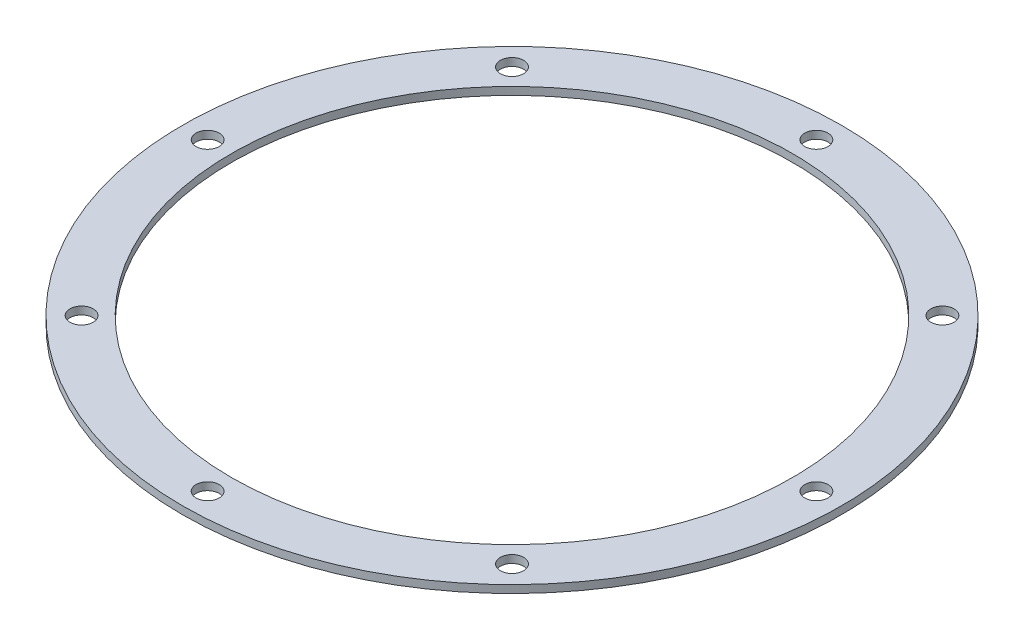
SolidWorks part; units mm, degrees
ref_plane "Front Plane" through (0, 0, 0) normal (0, 0, 1) x (1, 0, 0)
ref_plane "Top Plane" through (0, 0, 0) normal (0, 1, 0) x (1, 0, 0)
ref_plane "Right Plane" through (0, 0, 0) normal (1, 0, 0) x (0, 0, -1)
sketch "Sketch1" plane through (0, 0, 0) normal (0, 1, 0) x (1, 0, 0)
  circle A0 centre (0, 0) radius 72.375
  circle A1 centre (0, 0) radius 85
  circle A2 centre (0, 0) radius 78.5
  dimension "D1" = 157
  dimension "D2" = 170
  dimension "D3" = 144.75
extrude "Boss-Extrude1" add sketch "Sketch1" along normal blind 2 contours A1 A2 | A2 A0
sketch "Sketch2" plane through (0, 0, 0) normal (0, -1, 0) x (-1, 0, 0)
  circle A0 centre (0, 0) radius 78.5 construction
  circle A1 centre (0, 0) radius 78.5
  point P4 (0, 78.5)
  point P27 (55.5079, 55.5079)
  point P28 (78.5, 0)
  point P29 (55.5079, -55.5079)
  point P30 (0, -78.5)
  point P31 (-55.5079, -55.5079)
  point P32 (-78.5, 0)
  point P33 (-55.5079, 55.5079)
  dimension "D1" = 8
hole_wizard "Ø6.0mm Dowel Hole1" positions "Sketch2" profile "Sketch4" hole size "Ø6.0" standard "ANSI Metric" end condition through all
sketch "Sketch4" plane through (55.5079, 0, -55.5079) normal (1, 0, 0) x (0, 0, -1)
  line L0 (0, 0) -> (0, 2)
  line L1 (0, 2) -> (3, 2)
  line L2 (3, 2) -> (3, 0)
  line L5 (3, 0) -> (0, 0)
  line L11 (0, -6.35) -> (0, 107.95) construction
  dimension "Thru Hole Dia." = 6
  dimension "Thru Hole Depth" = 2
